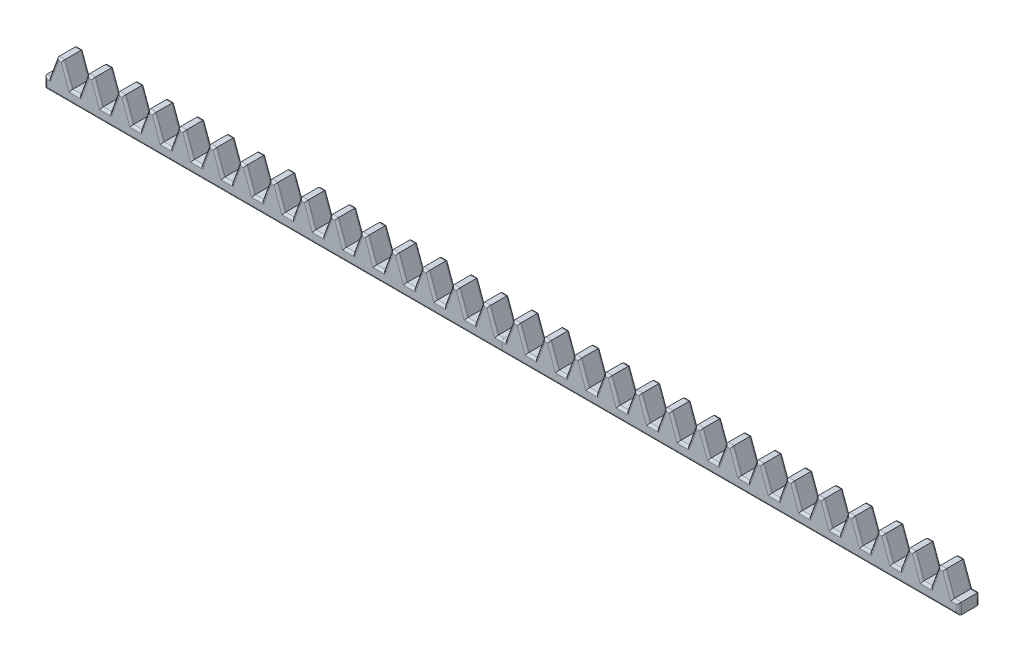
SolidWorks part; units mm, degrees
extrude "Blank" add sketch "BlankSke" against normal blind 8.89
sketch "BlankSke" plane through (0, 0, 0) normal (0, 0, 1) x (1, 0, 0)
  line L1 (0, 0) -> (400.0002, 0)
  line L2 (0, 0) -> (0, 14.3933)
  line L3 (0, 14.3933) -> (400.0002, 14.3933)
  line L4 (400.0002, 0) -> (400.0002, 14.3933)
  dimension "Length" = 400.0002
  dimension "Blank_height" = 14.3933
ref_plane "Plane1" through (0, 0, 0) normal (0, 0, 1) x (1, 0, 0)
ref_plane "Plane2" through (0, 0, 0) normal (0, 1, 0) x (1, 0, 0)
ref_plane "Plane3" through (0, 0, 0) normal (1, 0, 0) x (0, 0, -1)
sketch "HoldingSke" plane through (0, 0, 0) normal (0, 1, 0) x (1, 0, 0)
  line L0 (0, 0) -> (116.7452, -97.9608)
  line L1 (-15, 0) -> (100, 0) construction
  line L2 (0, 0) -> (-2.1039, 2.3779)
  line L3 (0, 0) -> (-11.863, 4.5341)
  line L4 (0, 0) -> (6.5177, 5.6657)
  line L5 (0, 0) -> (-23.7986, -8.8762)
  line L6 (0, 0) -> (-10.5278, -7.1032)
  line L9 (-71.009, 38.7566) -> (417.6302, 216.6067)
  line L10 (-76.2, 71.12) -> (-66.04, 71.12)
  line L11 (0, 0) -> (-8.89, 0)
  line L12 (-76.2, 101.6) -> (-76.0298, 101.6)
  line L13 (24.9733, 27.94) -> (52.9518, 28.4284)
  line L14 (24.9733, 27.94) -> (24.9746, 27.94)
  line L15 (24.9733, 27.94) -> (100.4006, 29.5858)
  circle A0 centre (0, 0) radius 19.05
  circle A1 centre (0, 0) radius 5.08
  circle A2 centre (0, 0) radius 12.7
  dimension "MPH" = 10.16
  dimension "Diameter" = 38.1
  dimension "Num_teeth" = 41
  dimension "Pitch" = 152.4
  dimension "Show_teeth" = 400
  dimension "Thickness" = 12.7
  dimension "Ap" = 20
  dimension "Pitch_height" = 10.16
  dimension "Width" = 8.89
  dimension "Backlash" = 0.1702
  dimension "Addendum_fac" = 1
  dimension "Dedendum_fac" = 1.25
  dimension "Clearance_fac" = 0.25
  dimension "Dedendum_add" = 0.0013
  dimension "Length" = 519.999
sketch "TooCutSkeIll" plane through (0, 0, 0) normal (0, 0, 1) x (1, 0, 0)
  line L0 (-5.3356, 14.2819) -> (-2.1631, 5.5655)
  line L1 (-1.1674, 4.8683) -> (1.1674, 4.8683)
  line L2 (2.1631, 5.5655) -> (5.3356, 14.2819)
  line L3 (400.0002, 14.3933) -> (0, 14.3933) construction
  line L4 (0, 0) -> (0, 64.897) construction
  line L5 (-13.208, 10.16) -> (12.954, 10.16) construction
  line L6 (0, 0) -> (400.0002, 0) construction
  line L7 (3.8354, 10.16) -> (3.8354, 48.7463) construction
  line L8 (-3.8354, 10.16) -> (-3.8354, 48.7463) construction
  line L9 (5.4948, 14.3933) -> (5.4948, 14.4187)
  line L10 (-5.4948, 14.3933) -> (-5.4948, 14.4187)
  line L11 (-5.4948, 14.4187) -> (5.4948, 14.4187)
  arc A0 (1.1674, 4.8683) -> (2.1631, 5.5655) centre (1.1674, 5.9279) ccw
  arc A1 (-2.1631, 5.5655) -> (-1.1674, 4.8683) centre (-1.1674, 5.9279) ccw
  arc A2 (5.4948, 14.3933) -> (5.3356, 14.2819) centre (5.4948, 14.224) ccw
  arc A3 (-5.3356, 14.2819) -> (-5.4948, 14.3933) centre (-5.4948, 14.224) ccw
  dimension "Pitch_height" = 10.16
  dimension "Addendum_plus" = 4.2587
  dimension "Pressure_angle" = 20
  dimension "Gap_width" = 7.6708
  dimension "Dedendum" = 5.2917
extrude "ToothCutIll" [suppressed] cut sketch "TooCutSkeIll" against normal through all
sketch "TooCutSkeSim" plane through (0, 0, 0) normal (0, 0, 1) x (1, 0, 0)
  line L0 (1.9094, 4.8683) -> (-1.9094, 4.8683)
  line L1 (5.3854, 14.4187) -> (1.9094, 4.8683)
  line L2 (0, 17.4625) -> (0, 53.467) construction
  line L3 (5.3854, 14.4187) -> (-5.3854, 14.4187)
  line L6 (-5.3854, 14.4187) -> (-1.9094, 4.8683)
  line L9 (-3.8354, 10.16) -> (3.8354, 10.16) construction
  line L10 (0, 0) -> (400.0002, 0) construction
  line L11 (3.8354, 10.16) -> (3.8354, 53.467) construction
  line L12 (-3.8354, 10.16) -> (-3.8354, 53.467) construction
  dimension "Pitch_height" = 10.16
  dimension "Addendum_plus" = 4.2587
  dimension "Pressure_angle" = 20
  dimension "Gap_width" = 7.6708
  dimension "Dedendum" = 5.2917
extrude "ToothCutSim" cut sketch "TooCutSkeSim" against normal through all
pattern_linear "TeethCuts" count 31 spacing 13.2994 along (1, 0, 0) of "ToothCutIll", "ToothCutSim"
ref_plane "Plane4" through (200.0001, 0, 0) normal (-1, 0, 0) x (0, 0, 1)
fillet "Fillet1" radius 1 74 edges at (400.0002, 2.4342, -8.89) (395.3395, 9.6308, -8.89) (392.3326, 14.3933, -8.89) (362.7268, 9.6308, -8.89) (359.084, 4.8683, -8.89) (328.8424, 9.6308, -8.89) (325.8355, 14.3933, -8.89) (319.1858, 4.8683, -8.89) (302.2436, 9.6308, -8.89) (282.9304, 9.6308, -8.89) (279.2876, 4.8683, -8.89) (275.6448, 9.6308, -8.89) (265.9882, 4.8683, -8.89) (252.6888, 4.8683, -8.89) (239.3894, 4.8683, -8.89) (235.7466, 9.6308, -8.89) (232.7397, 14.3933, -8.89) (206.1408, 14.3933, 0) (219.4402, 14.3933, 0) (226.09, 4.8683, 0) (229.7327, 9.6308, 0) (232.7397, 14.3933, 0) (239.3894, 4.8683, 0) (249.046, 9.6308, 0) (252.6888, 4.8683, 0) (262.3454, 9.6308, 0) (282.9304, 9.6308, 0) (296.2298, 9.6308, 0) (305.8864, 4.8683, 0) (309.5292, 9.6308, 0) (312.5361, 14.3933, 0) (319.1858, 4.8683, 0) (322.8286, 9.6308, 0) (336.128, 9.6308, 0) (352.4343, 14.3933, 0) (362.7268, 9.6308, 0) (368.7407, 9.6308, 0) (379.0332, 14.3933, 0) (385.6829, 4.8683, 0) (400.0002, 2.4342, 0) (200.0001, 0, 0) (182.5489, 9.6308, -8.89) (179.542, 14.3933, -8.89) (142.6507, 9.6308, -8.89) (139.6438, 14.3933, -8.89) (136.6369, 9.6308, -8.89) (132.9941, 4.8683, -8.89) (129.3513, 9.6308, -8.89) (119.6947, 4.8683, -8.89) (99.7456, 14.3933, -8.89) (96.7387, 9.6308, -8.89) (70.1398, 9.6308, -8.89) (66.497, 4.8683, -8.89) (49.5548, 9.6308, -8.89) (43.541, 9.6308, -8.89) (22.956, 9.6308, -8.89) (19.9491, 14.3933, -8.89) (9.6566, 9.6308, -8.89) (0.9547, 4.8683, -8.89) (0, 2.4342, -8.89) (0, 2.4342, 0) (6.6497, 14.3933, 0) (9.6566, 9.6308, 0) (13.2994, 4.8683, 0) (33.2485, 14.3933, 0) (39.8982, 4.8683, 0) (59.8473, 14.3933, 0) (73.1467, 14.3933, 0) (102.7525, 9.6308, 0) (149.9363, 9.6308, 0) (152.9432, 14.3933, 0) (182.5489, 9.6308, 0) (186.1917, 4.8683, 0) (192.8414, 14.3933, 0)
split "Split1" trim tools "Plane4" bodies to split 102 resulting bodies 103 104
equation "' \"Pitch@HoldingSke\" = 4"
equation "' \"Num_teeth@HoldingSke\" = 12"
equation "' \"Ap@HoldingSke\" =  20"
equation "' \"Ap@HoldingSke\" = 20"
equation "' \"Width@HoldingSke\" = 0.25"
equation "' \"Show_teeth@HoldingSke\" = 500"
equation "' \"Backlash@HoldingSke\" = 0.009"
equation "' \"Addendum_fac@HoldingSke\" = 1.0"
equation "' \"Dedendum_fac@HoldingSke\" = 1.25"
equation "' \"Dedendum_add@HoldingSke\" = 0.00005"
equation "' \"Clearance_fac@HoldingSke\" = 0.25"
equation "' \"Pitch_height@HoldingSke\" = 1"
equation "' \"Length@HoldingSke\" = 4.71"
equation "\"MPH@HoldingSke\" = \"Dedendum_fac@HoldingSke\" / \"Pitch@HoldingSke\" + 2 * \"Dedendum_add@HoldingSke\" + 0.002"
equation "\"MPH@HoldingSke\" = ((sgn( \"MPH@HoldingSke\" - \"Pitch_height@HoldingSke\")+1)*( \"MPH@HoldingSke\" - \"Pitch_height@HoldingSke\"))/2 + \"Pitch_height@HoldingSke\""
equation "\"Blank_height@BlankSke\" = \"Pitch_height@HoldingSke\" + \"Addendum_fac@HoldingSke\"  / \"Pitch@HoldingSke\" "
equation "\"Length@BlankSke\"=\"Drawer_length@Drawer Assembly Narrow.Assembly\"*0.0393701"
equation "\"Face_width@Blank\" = \"Width@HoldingSke\""
equation "\"Pressure_angle@TooCutSkeIll\" = \"Ap@HoldingSke\""
equation "\"Addendum_plus@TooCutSkeIll\" =  \"Addendum_fac@HoldingSke\"  / \"Pitch@HoldingSke\" + 0.001"
equation "\"Dedendum@TooCutSkeIll\" = \"Dedendum_fac@HoldingSke\"  / \"Pitch@HoldingSke\""
equation "\"Pitch_height@TooCutSkeIll\" =  \"MPH@HoldingSke\""
equation "\"Gap_width@TooCutSkeIll\" = 3.14159265 / 2 / \"Pitch@HoldingSke\" + 6 * \"Backlash@HoldingSke\""
equation "\"Pressure_angle@TooCutSkeSim\" = \"Ap@HoldingSke\""
equation "\"Addendum_plus@TooCutSkeSim\" =  \"Addendum_fac@HoldingSke\"  / \"Pitch@HoldingSke\" + 0.001"
equation "\"Dedendum@TooCutSkeSim\" = \"Dedendum_fac@HoldingSke\"  / \"Pitch@HoldingSke\""
equation "\"Pitch_height@TooCutSkeSim\" =  \"MPH@HoldingSke\""
equation "\"Gap_width@TooCutSkeSim\" = 3.14159265 / 2 / \"Pitch@HoldingSke\" + 6 * \"Backlash@HoldingSke\""
equation "\"Root_fillet@TooCutSkeIll\" = \"Clearance_fac@HoldingSke\" / \"Pitch@HoldingSke\" + \"Dedendum_add@HoldingSke\""
equation "\"Break_rad@TooCutSkeIll\" = 0.02 / \"Pitch@HoldingSke\" * 2"
equation "\"Linear_pitch@TeethCuts\" = 3.14159265 / \"Pitch@HoldingSke\""
equation "\"Num_teeth@HoldingSke\" = int( ( \"Length@HoldingSke\" + 0 ) / (3.14159265 / \"Pitch@HoldingSke\")) + 0.9999  + 1"
equation " \"Num_teeth@TeethCuts\" = int( \"Show_teeth@HoldingSke\" ) + 1"
equation " \"Num_teeth@TeethCuts\" = ((sgn( \"Num_teeth@TeethCuts\" - \"Num_teeth@HoldingSke\" )-1)*( \"Num_teeth@TeethCuts\" - \"Num_teeth@HoldingSke\" ))/-2+ \"Num_teeth@HoldingSke\""
equation " \"Num_teeth@TeethCuts\" = ((sgn( \"Num_teeth@TeethCuts\" - 2.0)+1)*( \"Num_teeth@TeethCuts\" - 2.0))/2 +2.0"
